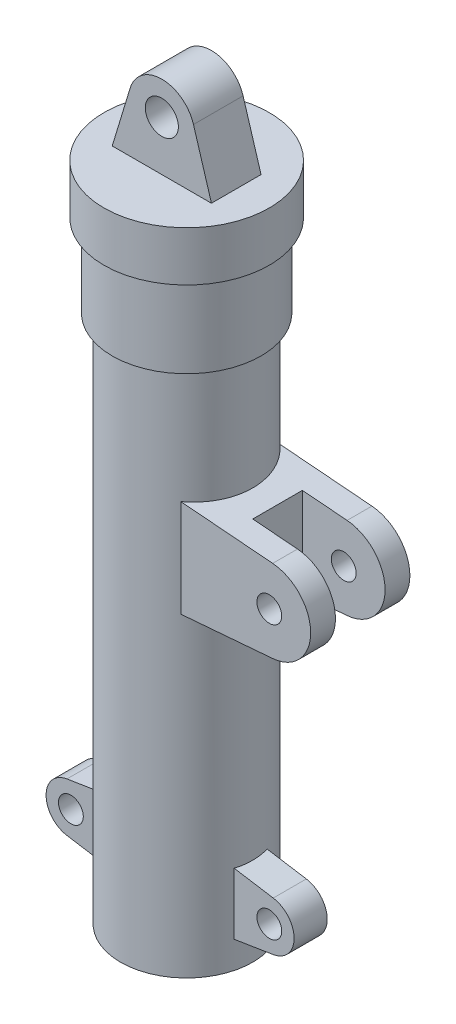
SolidWorks part; units mm, degrees
ref_plane "Plane1" through (0, 0, 0) normal (0, 0, 1) x (1, 0, 0)
ref_plane "Plane2" through (0, 0, 0) normal (0, 1, 0) x (1, 0, 0)
ref_plane "Plane3" through (0, 0, 0) normal (1, 0, 0) x (0, 0, -1)
other "Configuration Table"
sketch "Sketch1" plane through (0, 0, 0) normal (0, 0, 1) x (1, 0, 0)
  line L0 (22.5, -330) -> (40, -330)
  line L1 (0, 55) -> (0, 70)
  line L2 (50, 70) -> (0, 70)
  line L3 (40, -10) -> (40, -330)
  line L4 (45, -10) -> (45, 40)
  line L5 (50, 40) -> (50, 70)
  line L6 (50, 40) -> (45, 40)
  line L7 (45, -10) -> (40, -10)
  line L8 (22.5, -330) -> (22.5, -325)
  line L9 (22.5, -325) -> (35, -325)
  line L10 (35, -325) -> (35, 55)
  line L11 (35, 55) -> (0, 55)
  line L12 (0, 100) -> (0, -90) construction
  dimension "D1" = 400
  dimension "D2" = 50
  dimension "D3" = 40
  dimension "D4" = 35
  dimension "D5" = 22.5
  dimension "D6" = 5
  dimension "D7" = 15
  dimension "D8" = 30
  dimension "D9" = 5
  dimension "D10" = 80
revolve "Base-Revolve" add sketch "Sketch1" angle 360 about L12
sketch "Sketch2" plane through (0, 0, 0) normal (0, 0, 1) x (1, 0, 0)
  line L0 (19.1389, 105.8055) -> (30, 70)
  line L1 (50, 70) -> (-50, 70) construction
  line L2 (-19.1389, 105.8055) -> (-30, 70)
  line L3 (0, 100) -> (0, -90) construction
  line L4 (30, 70) -> (-30, 70)
  arc A0 (19.1389, 105.8055) -> (-19.1389, 105.8055) centre (0, 100) ccw
  circle A1 centre (0, 100) radius 10
  dimension "D2" = 20
  dimension "D3" = 20
  dimension "D1" = 60
  dimension "D5" = 30
extrude "Boss-Extrude1" add sketch "Sketch2" along normal mid plane 30
sketch "Sketch3" plane through (0, 0, 0) normal (0, 0, 1) x (1, 0, 0)
  line L0 (62.374, -280.189) -> (30, -275)
  line L1 (30, -275) -> (30, -315)
  line L3 (30, -315) -> (62.374, -309.811)
  line L4 (40, -330) -> (-40, -330) construction
  arc A0 (62.374, -280.189) -> (62.374, -309.811) centre (60, -295) cw
  circle A1 centre (60, -295) radius 7.5
  dimension "D2" = 15
  dimension "D4" = 15
  dimension "D1" = 40
  dimension "D3" = 30
  dimension "D5" = 35
  dimension "D6" = 30
extrude "Boss-Extrude2" add sketch "Sketch3" along normal mid plane 20
mirror "Mirror1" about plane through (0, 0, 0) normal (1, 0, 0) of "Boss-Extrude2"
sketch "Sketch8" plane through (0, 0, 0) normal (0, 0, 1) x (1, 0, 0)
  line L0 (82.0416, -85.0835) -> (20, -80)
  line L1 (20, -80) -> (20, -140)
  line L2 (45, -10) -> (-45, -10) construction
  line L3 (20, -140) -> (82.0416, -134.9165)
  arc A0 (82.0416, -85.0835) -> (82.0416, -134.9165) centre (80, -110) cw
  circle A1 centre (80, -110) radius 7.5
  dimension "D2" = 25
  dimension "D4" = 15
  dimension "D1" = 60
  dimension "D3" = 60
  dimension "D5" = 100
  dimension "D6" = 20
extrude "Boss-Extrude3" add sketch "Sketch8" along normal mid plane 60
sketch "Sketch4" plane through (0, 0, 0) normal (0, 0, 1) x (1, 0, 0)
  line L0 (0, -10) -> (35, -10)
  line L1 (0, -10) -> (0, -325)
  line L2 (35, -325) -> (0, -325)
  line L3 (35, -325) -> (35, -10)
  line L5 (35, -325) -> (-35, -325) construction
  line L6 (45, -10) -> (-45, -10) construction
  line L7 (0, 0) -> (0, -130) construction
  dimension "D1" = 35
revolve "Cut-Revolve1" cut sketch "Sketch4" angle 360 about L7
sketch "Sketch9" plane through (0, 0, 0) normal (0, 0, 1) x (1, 0, 0)
  line L0 (55, -70) -> (125, -70)
  line L1 (55, -70) -> (55, -150)
  line L2 (125, -150) -> (55, -150)
  line L3 (125, -150) -> (125, -70)
  arc A0 (82.0416, -134.9165) -> (82.0416, -85.0835) centre (80, -110) ccw construction
  dimension "D1" = 80
  dimension "D2" = 70
  dimension "D3" = 25
  dimension "D4" = 40
extrude "Cut-Extrude1" cut sketch "Sketch9" against normal mid plane 30
